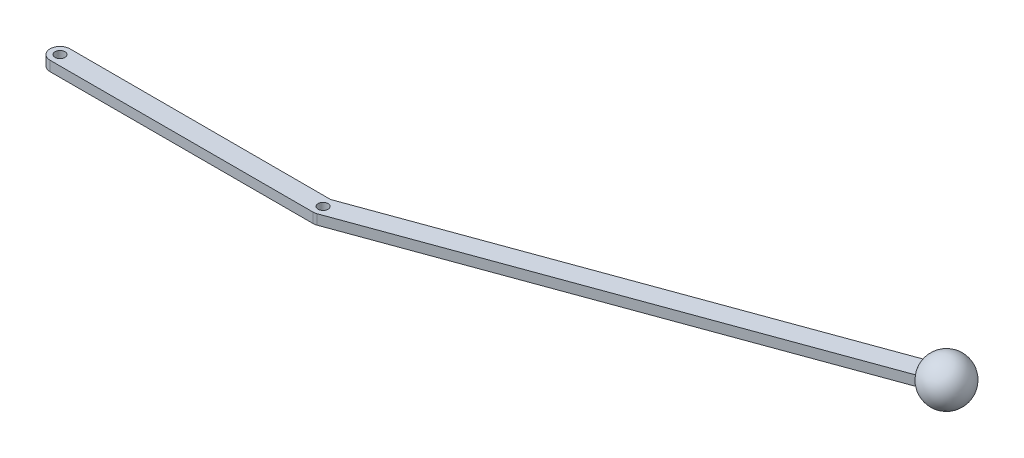
SolidWorks part; units mm, degrees
ref_plane "Front Plane" through (0, 0, 0) normal (0, 0, 1) x (1, 0, 0)
ref_plane "Top Plane" through (0, 0, 0) normal (0, 1, 0) x (1, 0, 0)
ref_plane "Right Plane" through (0, 0, 0) normal (1, 0, 0) x (0, 0, -1)
sketch "Sketch1" plane through (0, 0, 0) normal (0, 1, 0) x (1, 0, 0)
  line L0 (0, 0) -> (-265, 0) construction
  line L1 (0, 0) -> (460.4494, 167.5899) construction
  line L2 (-3.4202, 9.3969) -> (457.0292, 176.9868) construction
  line L3 (-3.4202, 9.3969) -> (3.4202, -9.3969) construction
  line L4 (457.0292, 176.9868) -> (463.8696, 158.1929) construction
  line L5 (3.4202, -9.3969) -> (463.8696, 158.1929) construction
  line L6 (-3.4202, 9.3969) -> (463.8696, 158.1929) construction
  line L7 (457.0292, 176.9868) -> (3.4202, -9.3969) construction
  line L8 (0, -10) -> (-265, -10) construction
  line L9 (0, -10) -> (0, 10) construction
  line L10 (-265, -10) -> (-265, 10) construction
  line L11 (0, 10) -> (-265, 10) construction
  line L12 (0, -10) -> (-265, 10) construction
  line L13 (-265, -10) -> (0, 10) construction
  line L14 (-265, 10) -> (-2.2245, 9.8321)
  line L15 (-2.2245, 9.8321) -> (457.0292, 176.9868)
  line L16 (463.8696, 158.1929) -> (3.4202, -9.3969)
  line L17 (0, -10) -> (-265, -10)
  arc A0 (-265, -10) -> (-265, 10) centre (-265, 0) cw
  arc A1 (457.0292, 176.9868) -> (463.8696, 158.1929) centre (460.4494, 167.5899) cw
  arc A2 (3.4202, -9.3969) -> (0, -10) centre (0, 0) cw
  circle A3 centre (-265, 0) radius 5
  circle A4 centre (0, 0) radius 5
  circle A5 centre (460.4494, 167.5899) radius 5
  point P5 (230.2247, 83.7949)
  point P6 (-132.5, 0)
  dimension "D5" = 10
  dimension "D6" = 10
  dimension "D7" = 10
  dimension "D1" = 265
  dimension "D2" = 490
  dimension "D3" = 20
  dimension "D4" = 20
extrude "Boss-Extrude1" add sketch "Sketch1" along normal mid plane 10 contours A2 L16 A1 L15 L14 A0 L17 A5 A4 A3
sketch "Sketch2" plane through (0, 0, 0) normal (0, 1, 0) x (1, 0, 0)
  circle A0 centre (460.4494, 167.5899) radius 5
extrude "Boss-Extrude2" add sketch "Sketch2" along normal mid plane 10
sketch "Sketch3" plane through (0, 0, 0) normal (0, 1, 0) x (1, 0, 0)
  line L1 (453.6926, 189.0514) -> (467.2062, 146.1284)
  arc A0 (467.2062, 146.1284) -> (453.6926, 189.0514) centre (460.4494, 167.5899) ccw
  dimension "D1" = 45
revolve "Revolve1" add sketch "Sketch3" angle 360 about L1
